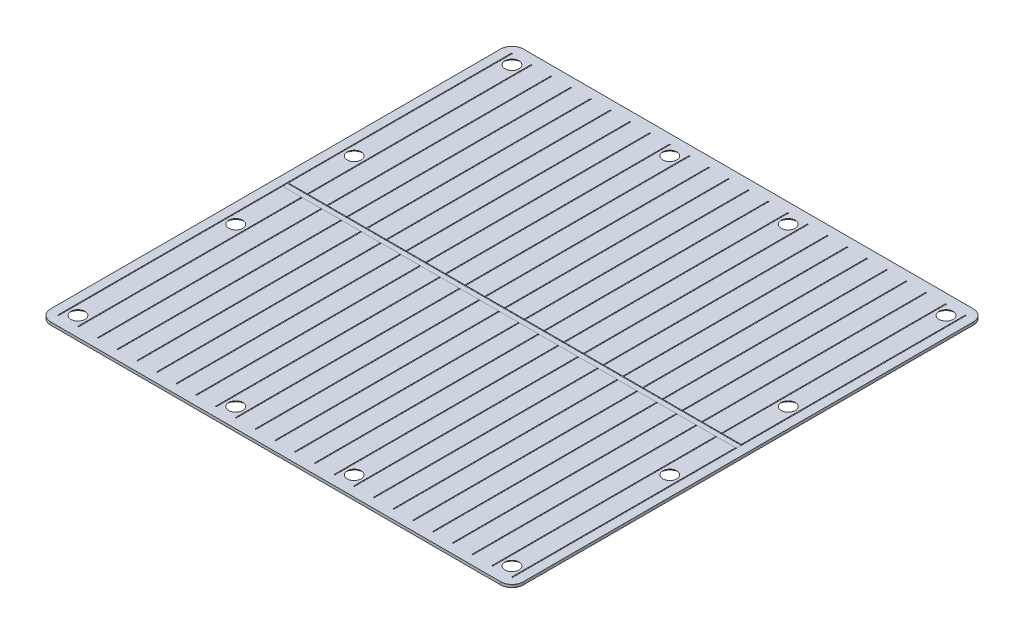
SolidWorks part; units mm, degrees
material "99.5% Aluminum Oxide"
ref_plane "Front Plane" through (0, 0, 0) normal (0, 0, 1) x (1, 0, 0)
ref_plane "Top Plane" through (0, 0, 0) normal (0, 1, 0) x (1, 0, 0)
ref_plane "Right Plane" through (0, 0, 0) normal (1, 0, 0) x (0, 0, -1)
sketch "Sketch1" plane through (0, 0, 0) normal (0, 1, 0) x (1, 0, 0)
  line L1 (-125, -125) -> (125, -125)
  line L2 (-125, -125) -> (-125, 125)
  line L3 (-125, 125) -> (125, 125)
  line L4 (125, -125) -> (125, 125)
  line L5 (-125, -125) -> (125, 125) construction
  line L6 (-125, 125) -> (125, -125) construction
  point P0 (0, 0)
  dimension "D1" = 250
extrude "Boss-Extrude1" add sketch "Sketch1" along normal blind 1.5
sketch "EDS_Wiring Sketch" plane through (0, 1.5, 0) normal (0, 1, 0) x (1, 0, 0)
  line L0 (-120, 120) -> (-120, -120)
  line L1 (-125, 125) -> (-125, -125) construction
  line L2 (-109.5652, 120) -> (-109.5652, -120)
  line L3 (-99.1304, 120) -> (-99.1304, -120)
  line L4 (-88.6957, 120) -> (-88.6957, -120)
  line L5 (-78.2609, 120) -> (-78.2609, -120)
  line L6 (-67.8261, 120) -> (-67.8261, -120)
  line L7 (-57.3913, 120) -> (-57.3913, -120)
  line L8 (-46.9565, 120) -> (-46.9565, -120)
  line L9 (-36.5217, 120) -> (-36.5217, -120)
  line L10 (-26.087, 120) -> (-26.087, -120)
  line L11 (-15.6522, 120) -> (-15.6522, -120)
  line L12 (-5.2174, 120) -> (-5.2174, -120)
  line L13 (5.2174, 120) -> (5.2174, -120)
  line L14 (15.6522, 120) -> (15.6522, -120)
  line L15 (26.087, 120) -> (26.087, -120)
  line L16 (36.5217, 120) -> (36.5217, -120)
  line L17 (46.9565, 120) -> (46.9565, -120)
  line L18 (57.3913, 120) -> (57.3913, -120)
  line L19 (67.8261, 120) -> (67.8261, -120)
  line L20 (78.2609, 120) -> (78.2609, -120)
  line L21 (88.6957, 120) -> (88.6957, -120)
  line L22 (99.1304, 120) -> (99.1304, -120)
  line L23 (109.5652, 120) -> (109.5652, -120)
  line L24 (120, 120) -> (120, -120)
  line L25 (125, -125) -> (125, 125) construction
  line L26 (-120, 0) -> (120, 0)
  point P4 (-120, 0)
  dimension "D1" = 240
  dimension "D2" = 5
  dimension "D4" = 5
  dimension "D3" = 24
sketch "Sketch3" plane through (0, 0, 125) normal (0, 0, 1) x (1, 0, 0)
  circle A0 centre (-120, 1.5) radius 0.25
  dimension "D1" = 0.5
extrude "Cut-Extrude1" cut sketch "Sketch3" against normal up to vertex (245 mm away) from vertex at -5 starting at point (-120, 1.5, 120)
pattern_linear "LPattern1" count 24 spacing 10.4348 along (1, 0, 0) of "Cut-Extrude1"
sketch "Sketch4" plane through (-125, 0, 0) normal (-1, 0, 0) x (0, 0, 1)
  line L0 (-1.5, 1.5) -> (1.5, 1.5)
  line L1 (-120, 1.5) -> (120, 1.5) construction
  line L2 (-1.25, 1.25) -> (1.25, 1.25)
  arc A0 (-1.5, 1.5) -> (-1.25, 1.25) centre (-1.25, 1.5) ccw
  arc A1 (1.5, 1.5) -> (1.25, 1.25) centre (1.25, 1.5) cw
  point P4 (0, 1.5)
  dimension "D1" = 0.25
  dimension "D2" = 3
extrude "Cut-Extrude2" cut sketch "Sketch4" against normal up to vertex (245 mm away) from vertex at -5 starting at point (-120, 1.5, 0)
sketch "Hole_Layout_Sketch" plane through (0, 0, 0) normal (0, -1, 0) x (1, 0, 0)
  line L0 (26.337, 1.5) -> (26.337, 120) construction
  line L1 (36.2717, 120) -> (36.2717, 1.5) construction
  line L2 (109.8152, 1.5) -> (109.8152, 120) construction
  line L3 (119.75, 120) -> (119.75, 1.5) construction
  line L4 (26.337, 1.5) -> (26.337, 120) construction
  line L5 (36.2717, 120) -> (36.2717, 1.5) construction
  line L6 (109.8152, 1.5) -> (109.8152, 120) construction
  line L7 (119.75, 120) -> (119.75, 1.5) construction
  line L8 (0, 0) -> (-50000, 0) construction
  line L9 (0, 0) -> (0, 50000) construction
  line L10 (125, 125) -> (-35230.3391, -35230.3391) construction
  line L11 (119.75, 114.7826) -> (109.8152, 114.7826) construction
  line L12 (36.2717, 114.7826) -> (26.337, 114.7826) construction
  point P18 (114.7826, 114.7826)
  point P19 (31.3043, 114.7826)
  point P23 (-114.7826, 114.7826)
  point P24 (-31.3043, 114.7826)
  point P26 (-114.7826, -114.7826)
  point P27 (-31.3043, -114.7826)
  point P28 (31.3043, -114.7826)
  point P29 (114.7826, -114.7826)
  point P31 (-114.7826, 31.3043)
  point P32 (-114.7826, -31.3043)
  point P33 (114.7826, -31.3043)
  point P34 (114.7826, 31.3043)
hole_wizard "CSK for M5 Flat Head Machine Screw1" positions "3DSketch1" profile "Sketch7" countersink size "M5" standard "ANSI Metric" end condition through all
sketch3d "3DSketch1"
  point P0 (-114.7826, 0, 114.7826)
  point P3 (-114.7826, 0, 31.3043)
  point P6 (-114.7826, 0, -31.3043)
  point P9 (-114.7826, 0, -114.7826)
  point P12 (-31.3043, 0, -114.7826)
  point P15 (31.3043, 0, -114.7826)
  point P18 (31.3043, 0, 114.7826)
  point P21 (-31.3043, 0, 114.7826)
  point P24 (114.7826, 0, 114.7826)
  point P27 (114.7826, 0, 31.3043)
  point P30 (114.7826, 0, -31.3043)
  point P33 (114.7826, 0, -114.7826)
sketch "Sketch7" plane through (-114.7826, 0, 114.7826) normal (1, 0, 0) x (0, 0, -1)
  line L0 (0, 0) -> (0, 1.5)
  line L1 (0, 1.5) -> (2.75, 1.5)
  line L2 (2.75, 1.5) -> (2.75, 2.45)
  line L3 (2.75, 2.45) -> (5.2, 0)
  line L5 (5.2, 0) -> (0, 0)
  line L6 (-2.75, 2.45) -> (-5.2, 0) construction
  line L11 (0, -6.35) -> (0, 107.95) construction
  dimension "Thru Hole Dia." = 5.5
  dimension "Thru Hole Depth" = 1.5
  dimension "Near C'Sink Dia." = 10.4
  dimension "Near C'Sink Angle" = 90
fillet "Fillet1" radius 6 4 edges at (125, 0.75, 125) (-125, 0.75, 125) (125, 0.75, -125) (-125, 0.75, -125)
